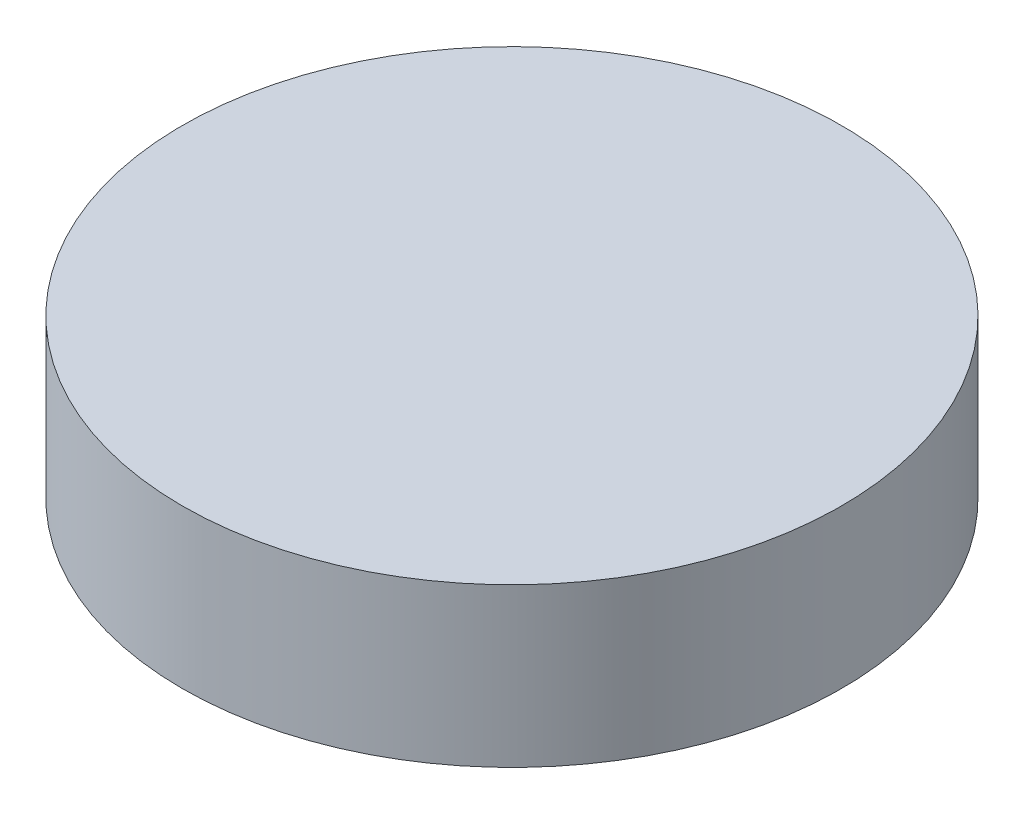
SolidWorks part; units mm, degrees
ref_plane "Front Plane" through (0, 0, 0) normal (0, 0, 1) x (1, 0, 0)
ref_plane "Top Plane" through (0, 0, 0) normal (0, 1, 0) x (1, 0, 0)
ref_plane "Right Plane" through (0, 0, 0) normal (1, 0, 0) x (0, 0, -1)
other "Configuration Table"
sketch "Sketch1" plane through (0, 0, 0) normal (0, 1, 0) x (1, 0, 0)
  circle A0 centre (650, 770) radius 25
extrude "OVEN_ayar_ayagi_4" add sketch "Sketch1" along normal blind 12 separate body
